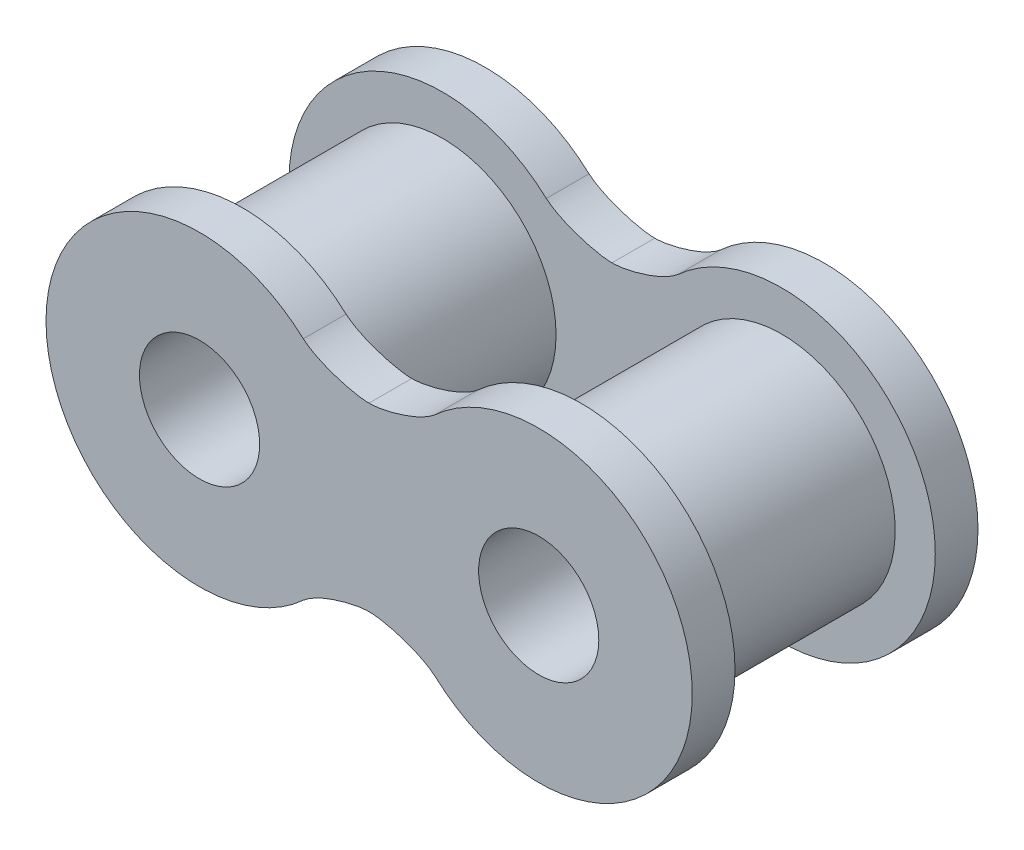
SolidWorks part; units mm, degrees
ref_plane "前视基准面" through (0, 0, 0) normal (0, 0, 1) x (1, 0, 0)
ref_plane "上视基准面" through (0, 0, 0) normal (0, 1, 0) x (1, 0, 0)
ref_plane "右视基准面" through (0, 0, 0) normal (1, 0, 0) x (0, 0, -1)
sketch "草图1" plane through (0, 0, 0) normal (0, 0, 1) x (1, 0, 0)
  line L0 (-6.35, 0) -> (66.7351, 0) construction
  line L1 (0, 69.5952) -> (0, 0) construction
  circle A0 centre (-6.35, 0) radius 4.25
  circle A1 centre (-6.35, 0) radius 2.25
  circle A2 centre (6.35, 0) radius 2.25
  circle A3 centre (6.35, 0) radius 4.25
  point P10 (66.7351, 0)
  point P11 (-39.6597, 0)
  dimension "D1" = 4.5
  dimension "D2" = 8.5
  dimension "D3" = 12.7
extrude "凸台-拉伸1" add sketch "草图1" along normal blind 3.75
sketch "草图2" plane through (0, 0, 3.75) normal (0, 0, 1) x (1, 0, 0)
  line L0 (0, 35.0813) -> (0, 0) construction
  line L1 (-6.35, 0) -> (6.35, 0) construction
  circle A0 centre (-6.35, 0) radius 5.75
  circle A1 centre (6.35, 0) radius 5.75
  circle A2 centre (-6.35, 0) radius 2.25 construction
  circle A3 centre (-6.35, 0) radius 2.25
  circle A4 centre (6.35, 0) radius 2.25 construction
  circle A5 centre (6.35, 0) radius 2.25
  spline S0 degree 3 poles (-2.4645, 4.2386) (-1.8011, 3.6779) (-0.3708, 3.3459) (0, 3.3864) knots 0 0 0 0 1 1 1 1
  spline S1 degree 3 poles (2.4645, 4.2386) (1.8011, 3.6779) (0.3708, 3.3459) (0, 3.3864) knots 0 0 0 0 1 1 1 1
  spline S2 degree 3 poles (2.4645, -4.2386) (1.8011, -3.6779) (0.3708, -3.3459) (0, -3.3864) knots 0 0 0 0 1 1 1 1
  spline S3 degree 3 poles (-2.4645, -4.2386) (-1.8011, -3.6779) (-0.3708, -3.3459) (0, -3.3864) knots 0 0 0 0 1 1 1 1
  point P3 (-2.8105, 10.5853)
  point P24 (-3.3445, 4.9668)
  point P25 (0, 3.2651)
  point P26 (-0.8225, 3.5987)
  point P27 (0, 3.7054)
  point P28 (-2.4466, 4.2819)
  point P29 (0, 3.4532)
  point P30 (-0.709, 3.694)
  point P31 (-3.0281, 5.1379)
  point P32 (-1.2826, 3.9125)
  point P33 (0, 0)
  point P34 (0, 3.5299)
  point P35 (0, 3.5373)
  point P36 (0, 3.5373)
  point P37 (-2.4333, 4.2097)
  point P38 (0, 3.4724)
  point P39 (-0.6331, 3.5103)
  point P40 (0, 3.3864)
  circle M5 centre (-6.35, 0) radius 4.25
  circle M6 centre (-6.35, 0) radius 2.25
  dimension "D1" = 11.5
extrude "凸台-拉伸3" add sketch "草图2" along normal blind 1.6 contours M5 M6 | A0 M5 | A0 S3 S2 A1 S1 S0 | A1 A5
ref_plane "基准面1" through (0, 0, 0) normal (0, 0, -1) x (-1, 0, 0)
mirror "镜向2" about plane through (0, 0, 0) normal (0, 0, -1) of "凸台-拉伸3", "凸台-拉伸1"
